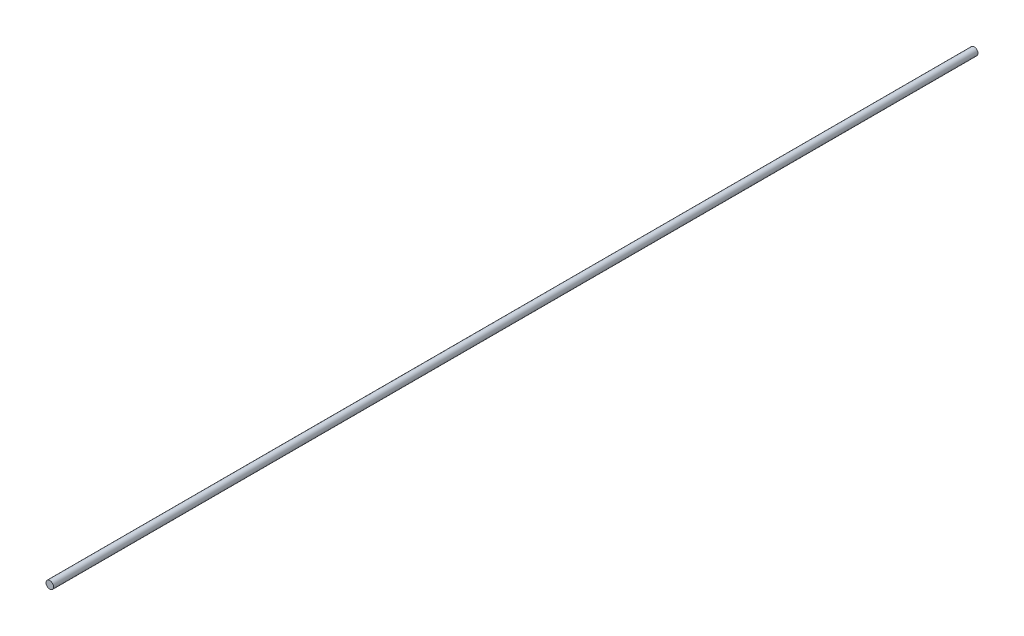
SolidWorks part; units mm, degrees
material "Hexcel AS4C (3000 Filaments)"
ref_plane "Front Plane" through (0, 0, 0) normal (0, 0, 1) x (1, 0, 0)
ref_plane "Top Plane" through (0, 0, 0) normal (0, 1, 0) x (1, 0, 0)
ref_plane "Right Plane" through (0, 0, 0) normal (1, 0, 0) x (0, 0, -1)
sketch "Sketch1" plane through (0, 0, 0) normal (0, 0, 1) x (1, 0, 0)
  circle A0 centre (0, 0) radius 2.5
  dimension "D1" = 5
extrude "Boss-Extrude1" add sketch "Sketch1" along normal blind 610
